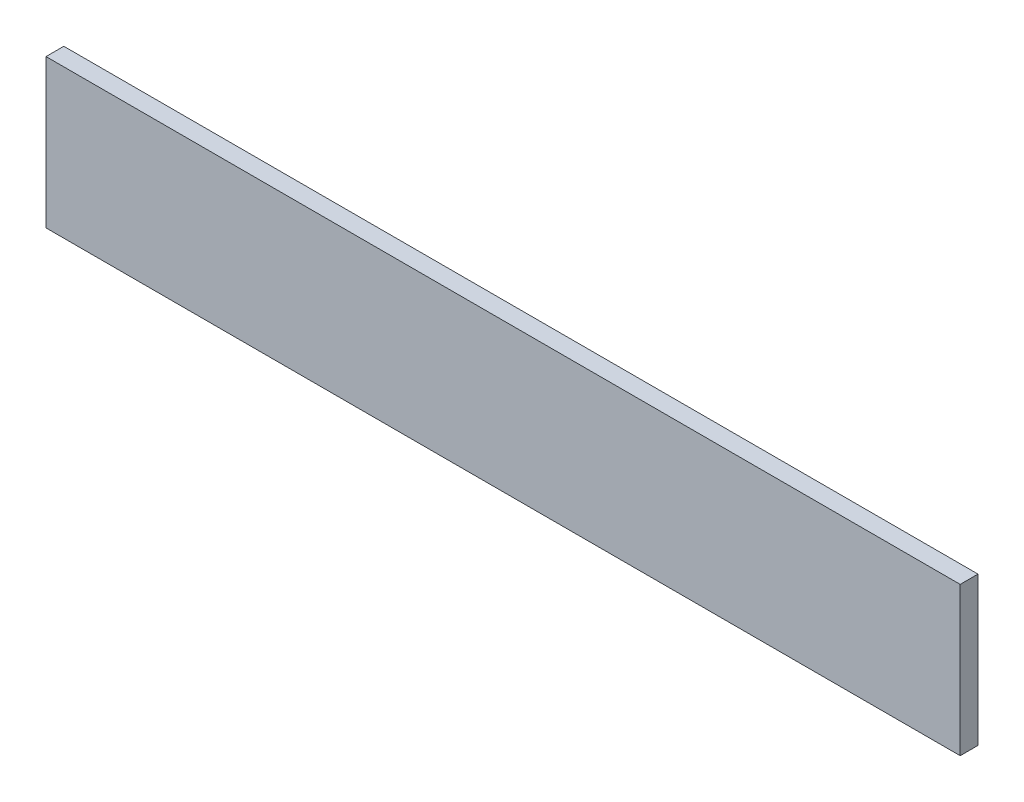
SolidWorks part; units mm, degrees
ref_plane "Front Plane" through (0, 0, 0) normal (0, 0, 1) x (1, 0, 0)
ref_plane "Top Plane" through (0, 0, 0) normal (0, 1, 0) x (1, 0, 0)
ref_plane "Right Plane" through (0, 0, 0) normal (1, 0, 0) x (0, 0, -1)
sketch "Sketch1" plane through (0, 0, 0) normal (0, 0, 1) x (1, 0, 0)
  line L1 (0, 0) -> (154, 0)
  line L2 (0, 0) -> (0, 25)
  line L3 (0, 25) -> (154, 25)
  line L4 (154, 0) -> (154, 25)
  dimension "D1" = 154
  dimension "D2" = 25
extrude "Profile" add sketch "Sketch1" along normal blind 3
equation "\"Profile_Depth\" = 3mm"
equation "\"D1@Profile\" = \"Profile_Depth\""
equation "\"EnvelopeWidth\" = 154mm"
equation "\"EnvelopeHeight\" = 25mm"
